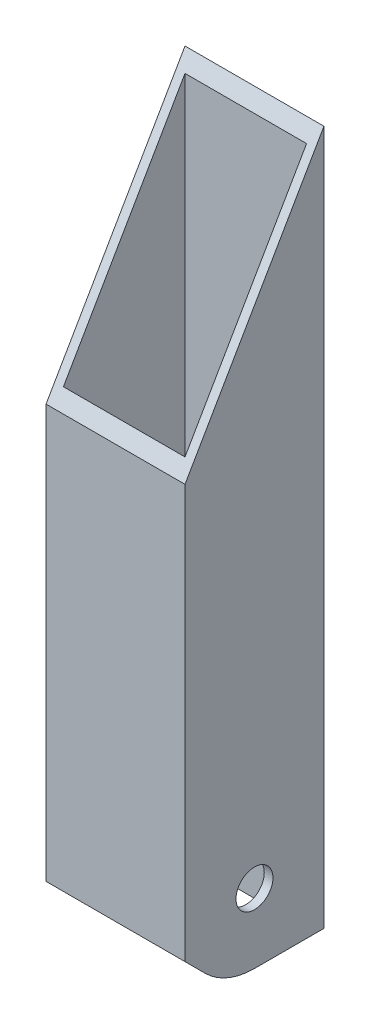
SolidWorks part; units mm, degrees
material "6061-T6 (SS)"
ref_plane "Front" through (0, 0, 0) normal (0, 0, 1) x (1, 0, 0)
ref_plane "Top" through (0, 0, 0) normal (0, 1, 0) x (1, 0, 0)
ref_plane "Right" through (0, 0, 0) normal (1, 0, 0) x (0, 0, -1)
sketch "Sketch1" plane through (0, 0, 0) normal (0, 1, 0) x (1, 0, 0)
  line L0 (-11.1125, 11.1125) -> (11.1125, 11.1125)
  line L1 (-12.7, -12.7) -> (12.7, -12.7)
  line L2 (-12.7, -12.7) -> (-12.7, 12.7)
  line L3 (-12.7, 12.7) -> (12.7, 12.7)
  line L4 (12.7, -12.7) -> (12.7, 12.7)
  line L5 (-12.7, -12.7) -> (12.7, 12.7) construction
  line L6 (-12.7, 12.7) -> (12.7, -12.7) construction
  line L7 (11.1125, -11.1125) -> (11.1125, 11.1125)
  line L8 (-11.1125, -11.1125) -> (11.1125, -11.1125)
  line L9 (-11.1125, -11.1125) -> (-11.1125, 11.1125)
  point P0 (0, 0)
  dimension "D1" = 25.4
  dimension "D2" = 25.4
  dimension "D3" = 1.5875
extrude "Extrude1" add sketch "Sketch1" along normal blind 127
sketch "Sketch3" plane through (12.7, 0, 0) normal (1, 0, 0) x (0, 0, -1)
  line L0 (12.7, 127) -> (-12.7, 127)
  line L2 (-12.7, 127) -> (-12.7, 83.0059)
  line L3 (-12.7, 127) -> (-12.7, 0) construction
  line L5 (-12.7, 83.0059) -> (12.7, 127)
  dimension "D1" = 60
extrude "Extrude3" cut sketch "Sketch3" against normal through all
hole_wizard "1/4 Clearance Hole1" positions "Sketch5" profile "Sketch4" hole size "1/4" standard "Ansi Inch" end condition through all
sketch "Sketch5" plane through (12.7, 0, 0) normal (1, 0, 0) x (0, 0, -1)
  line L0 (-12.7, 12.7) -> (12.7, 12.7) construction
  line L1 (-12.7, 83.0059) -> (-12.7, 0) construction
  line L2 (12.7, 127) -> (12.7, 0) construction
  line L4 (-12.7, 0) -> (12.7, 0) construction
  point P0 (0, 12.7)
  dimension "D1" = 12.7
sketch "Sketch4" plane through (12.7, 12.7, 0) normal (0, 1, 0) x (0, 0, -1)
  line L0 (0, 0) -> (0, 25.4)
  line L1 (0, 25.4) -> (3.3782, 25.4)
  line L2 (3.3782, 25.4) -> (3.3782, 0)
  line L5 (3.3782, 0) -> (0, 0)
  line L11 (0, -6.35) -> (0, 107.95) construction
  dimension "Thru Hole Dia." = 6.7564
  dimension "Thru Hole Depth" = 25.4
sketch "Sketch7" plane through (12.7, 0, 0) normal (1, 0, 0) x (0, 0, -1)
  line L0 (-5.2605, 0) -> (-12.7, 7.4395)
  line L1 (-12.7, 83.0059) -> (-12.7, 0) construction
  line L2 (-12.7, 7.4395) -> (-12.7, 0)
  line L3 (-12.7, 0) -> (-5.2605, 0)
  circle A0 centre (0, 12.7) radius 12.7 construction
extrude "Extrude4" cut sketch "Sketch7" against normal through all
sketch "Sketch8" plane through (12.7, 0, 0) normal (1, 0, 0) x (0, 0, -1)
  line L0 (-5.2605, 0) -> (-12.7, 7.4395) construction
  line L1 (0, 0) -> (-5.2605, 0)
  line L2 (-5.2605, 0) -> (-8.9803, 3.7197)
  arc A0 (0, 0) -> (-8.9803, 3.7197) centre (0, 12.7) cw
extrude "Extrude5" cut sketch "Sketch8" against normal through all
